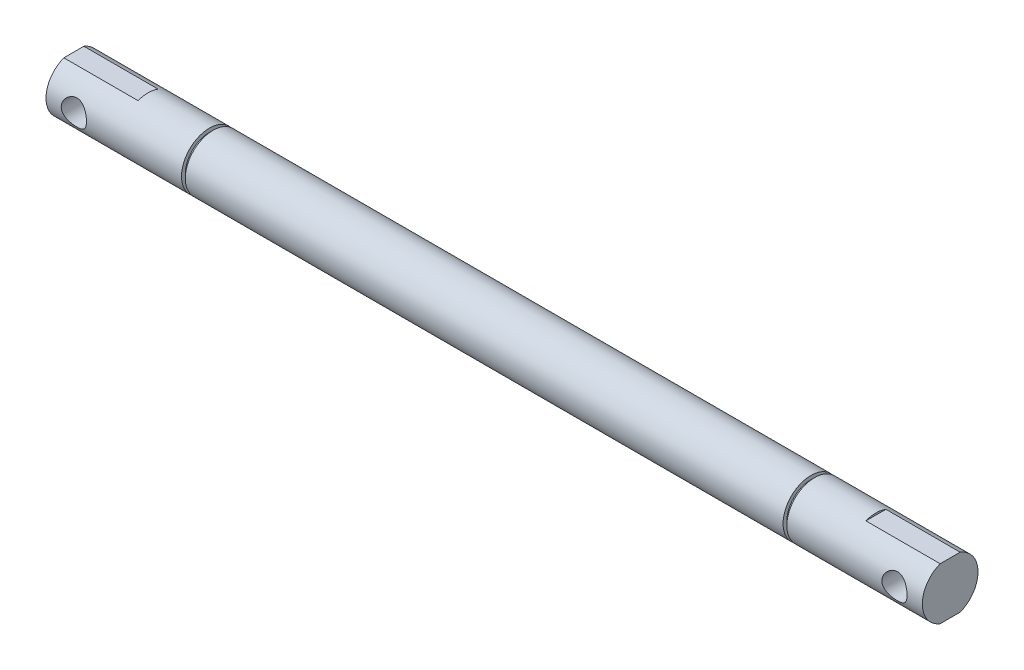
SolidWorks part; units mm, degrees
material "AISI 304"
ref_plane "Ön Düzlem" through (0, 0, 0) normal (0, 0, 1) x (1, 0, 0)
ref_plane "Üst Düzlem" through (0, 0, 0) normal (0, 1, 0) x (1, 0, 0)
ref_plane "Sağ Düzlem" through (0, 0, 0) normal (1, 0, 0) x (0, 0, -1)
sketch "Çizim1" plane through (0, 0, 0) normal (1, 0, 0) x (0, 0, -1)
  circle A0 centre (0, 0) radius 7.5
  dimension "D1" = 15
extrude "Yükseklik-Ekstrüzyon1" add sketch "Çizim1" along normal mid plane 236
sketch "Çizim2" plane through (0, 0, 0) normal (0, 0, 1) x (1, 0, 0)
  line L0 (118, 7.5) -> (-118, 7.5) construction
  line L1 (-81.5, 8.5) -> (-80.5, 8.5)
  line L2 (-81.5, 8.5) -> (-81.5, 6.5)
  line L3 (-81.5, 6.5) -> (-80.5, 6.5)
  line L4 (-80.5, 8.5) -> (-80.5, 6.5)
  line L5 (-81.5, 8.5) -> (-80.5, 6.5) construction
  line L6 (-81.5, 6.5) -> (-80.5, 8.5) construction
  line L7 (0, 0) -> (-41.0048, 0) construction
  point P0 (-81, 7.5)
  dimension "D1" = 81
  dimension "D2" = 1
  dimension "D3" = 1
revolve "Kes-Döndür2" cut sketch "Çizim2" angle 360 about L7
sketch "Çizim3" plane through (-118, 0, 0) normal (-1, 0, 0) x (0, 0, 1)
  line L0 (0, 0) -> (0, 7) construction
  line L1 (5.217, 7) -> (-5.217, 7)
  line L2 (-5.217, 7) -> (-0.676, 12.2128)
  line L3 (-0.676, 12.2128) -> (5.217, 7)
  point P6 (0, 7)
  dimension "D1" = 7
extrude "Kes-Ekstrüzyon1" cut sketch "Çizim3" against normal blind 20
mirror "Aynalama2" about plane through (0, 0, 0) normal (0, 1, 0) of "Kes-Ekstrüzyon1"
ref_plane "Düzlem2" through (0, 0, 12) normal (0, 0, 1) x (1, 0, 0)
hole_wizard "M8 Dişli Delik1" positions "Çizim10" profile "Çizim11" tap size "M8" standard "ISO" end condition through all
sketch "Çizim10" plane through (0, 0, 12) normal (0, 0, 1) x (1, 0, 0)
  line L0 (-118, 7) -> (-118, -7) construction
  point P0 (-110.5, 0)
  dimension "D1" = 7.5
sketch "Çizim11" plane through (-110.5, 0, 12) normal (1, 0, 0) x (0, -1, 0)
  line L0 (0, 0) -> (0, 19.5)
  line L1 (0, 19.5) -> (3.4, 19.5)
  line L2 (3.4, 19.5) -> (3.4, 0)
  line L5 (3.4, 0) -> (0, 0)
  line L11 (0, -6.35) -> (0, 107.95) construction
  dimension "Thru Tap Drill Dia." = 6.8
  dimension "Thru Tap Drill Depth" = 19.5
cosmetic thread "Delik Dişi1" parameters "D2"=8
mirror "Aynalama3" about plane through (0, 0, 0) normal (1, 0, 0) of "Kes-Döndür2", "Kes-Ekstrüzyon1", "Aynalama2", "M8 Dişli Delik1"
cosmetic thread "Delik Dişi2" parameters "D2"=8
